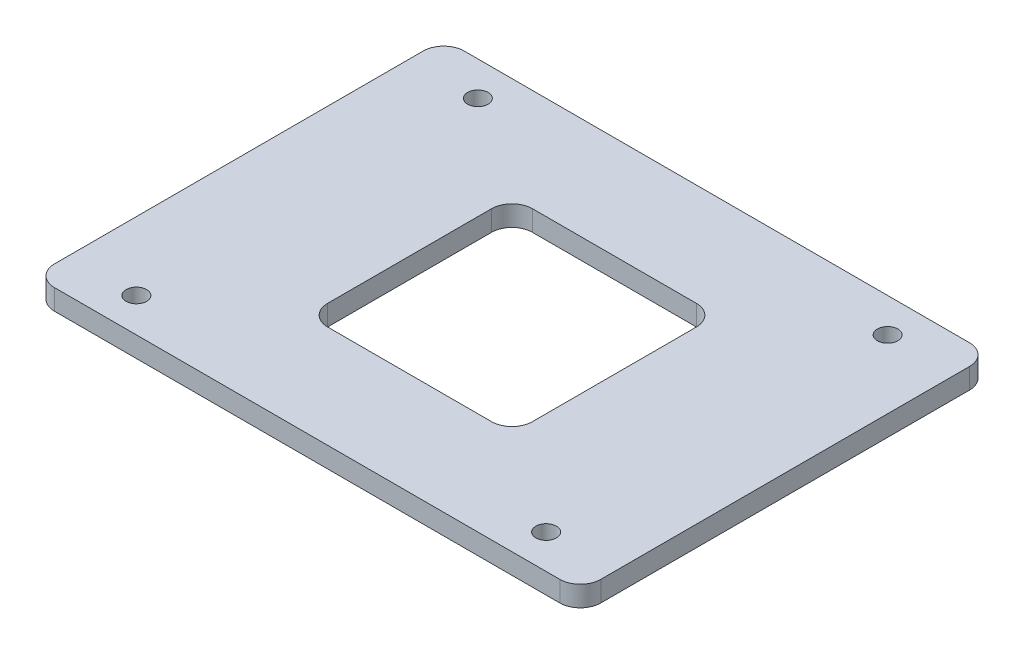
SolidWorks part; units mm, degrees
material "Thornel Mat VMA"
ref_plane "前视基准面" through (0, 0, 0) normal (0, 0, 1) x (1, 0, 0)
ref_plane "上视基准面" through (0, 0, 0) normal (0, 1, 0) x (1, 0, 0)
ref_plane "右视基准面" through (0, 0, 0) normal (1, 0, 0) x (0, 0, -1)
other "Configuration Table"
sketch "草图1" plane through (0, 0, 0) normal (0, 1, 0) x (1, 0, 0)
  line L0 (0, 0) -> (54.6094, 0) construction
  line L1 (-40, -30) -> (40, -30)
  line L2 (-40, -30) -> (-40, 30)
  line L3 (-40, 30) -> (40, 30)
  line L4 (40, -30) -> (40, 30)
  line L5 (-40, -30) -> (40, 30) construction
  line L6 (-40, 30) -> (40, -30) construction
  line L7 (0, 0) -> (0, 36.4453) construction
  line L9 (-15, -15) -> (15, -15)
  line L10 (-15, -15) -> (-15, 15)
  line L11 (-15, 15) -> (15, 15)
  line L12 (15, -15) -> (15, 15)
  line L13 (-15, -15) -> (15, 15) construction
  line L14 (-15, 15) -> (15, -15) construction
  circle A0 centre (-30, 25) radius 1.5
  circle A1 centre (30, 25) radius 1.5
  circle A2 centre (30, -25) radius 1.5
  circle A3 centre (-30, -25) radius 1.5
  point P0 (0, 0)
  dimension "D3" = 3
  dimension "D1" = 80
  dimension "D2" = 60
  dimension "D4" = 30
  dimension "D5" = 25
  dimension "D6" = 30
  dimension "D7" = 30
extrude "凸台-拉伸1" add sketch "草图1" along normal blind 3
fillet "圆角1" radius 3 4 edges at (-40, 1.5, -30) (-40, 1.5, 30) (40, 1.5, -30) (40, 1.5, 30)
fillet "圆角2" radius 3 4 edges at (-15, 1.5, -15) (-15, 1.5, 15) (15, 1.5, 15) (15, 1.5, -15)
